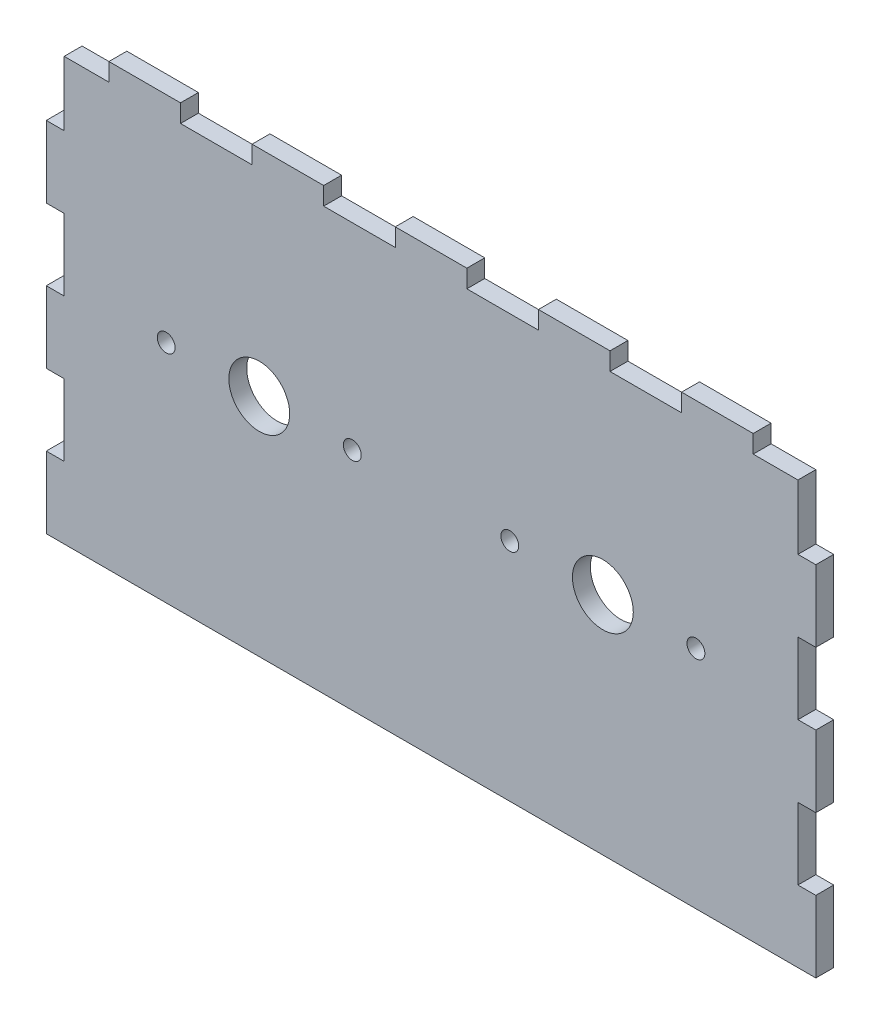
SolidWorks part; units mm, degrees
ref_plane "정면" through (0, 0, 0) normal (0, 0, 1) x (1, 0, 0)
ref_plane "윗면" through (0, 0, 0) normal (0, 1, 0) x (1, 0, 0)
ref_plane "우측면" through (0, 0, 0) normal (1, 0, 0) x (0, 0, -1)
sketch "스케치1" plane through (0, 0, 0) normal (0, 0, 1) x (1, 0, 0)
  line L0 (-48, 80.911) -> (-48, -78.9061) construction
  line L1 (-102.5, 59) -> (102.5, 59)
  line L2 (-102.5, 59) -> (-102.5, -59)
  line L3 (-102.5, -59) -> (102.5, -59)
  line L4 (102.5, 59) -> (102.5, -59)
  line L5 (-102.5, 59) -> (102.5, -59) construction
  line L6 (-102.5, -59) -> (102.5, 59) construction
  line L7 (48, 64.3355) -> (48, -72.4738) construction
  line L8 (0, 68.0997) -> (0, -64.9282) construction
  circle A0 centre (48, 4) radius 8.5
  circle A1 centre (-48, 4) radius 8.5
  circle A4 centre (-74, 4) radius 2.5
  circle A5 centre (-22, 4) radius 2.5
  circle A6 centre (22, 4) radius 2.5
  circle A7 centre (74, 4) radius 2.5
  point P0 (0, 0)
  point P24 (0, 0)
  dimension "D3" = 17
  dimension "D8" = 52
  dimension "D9" = 5
  dimension "D1" = 118
  dimension "D2" = 205
  dimension "D4" = 55
  dimension "D5" = 55
  dimension "D6" = 48
  dimension "D7" = 48
extrude "보스-돌출1" add sketch "스케치1" along normal blind 5
sketch "스케치2" plane through (0, 0, 5) normal (0, 0, 1) x (1, 0, 0)
  line L1 (-102.5, -59) -> (-107.5, -59)
  line L2 (-102.5, -59) -> (-102.5, -39)
  line L3 (-102.5, -39) -> (-107.5, -39)
  line L4 (-107.5, -59) -> (-107.5, -39)
  dimension "D1" = 5
  dimension "D2" = 20
extrude "보스-돌출2" add sketch "스케치2" against normal up to surface (5 mm away) up to face at (0, 0, 0)
pattern_linear "선형 패턴1" count 3 spacing 40 along (0, 1, 0) of "보스-돌출2"
mirror "대칭 복사1" about plane through (0, 0, 0) normal (1, 0, 0) of "선형 패턴1", "보스-돌출2"
sketch "스케치3" plane through (0, 0, 5) normal (0, 0, 1) x (1, 0, 0)
  line L0 (102.5, 59) -> (-102.5, 59) construction
  line L1 (10, 59) -> (-10, 59)
  line L2 (10, 59) -> (10, 64)
  line L3 (10, 64) -> (-10, 64)
  line L4 (-10, 59) -> (-10, 64)
  line L5 (0, 197.1917) -> (0, -69.1917) construction
  point P9 (0, 64)
  dimension "D1" = 20
  dimension "D2" = 5
extrude "보스-돌출3" add sketch "스케치3" against normal up to surface (5 mm away) up to face at (0, 0.8333, 0)
pattern_linear "선형 패턴2" count 3 spacing 40 along (1, 0, 0) of "보스-돌출3"
pattern_linear "선형 패턴3" count 3 spacing 40 along (-1, 0, 0) of "보스-돌출3"
